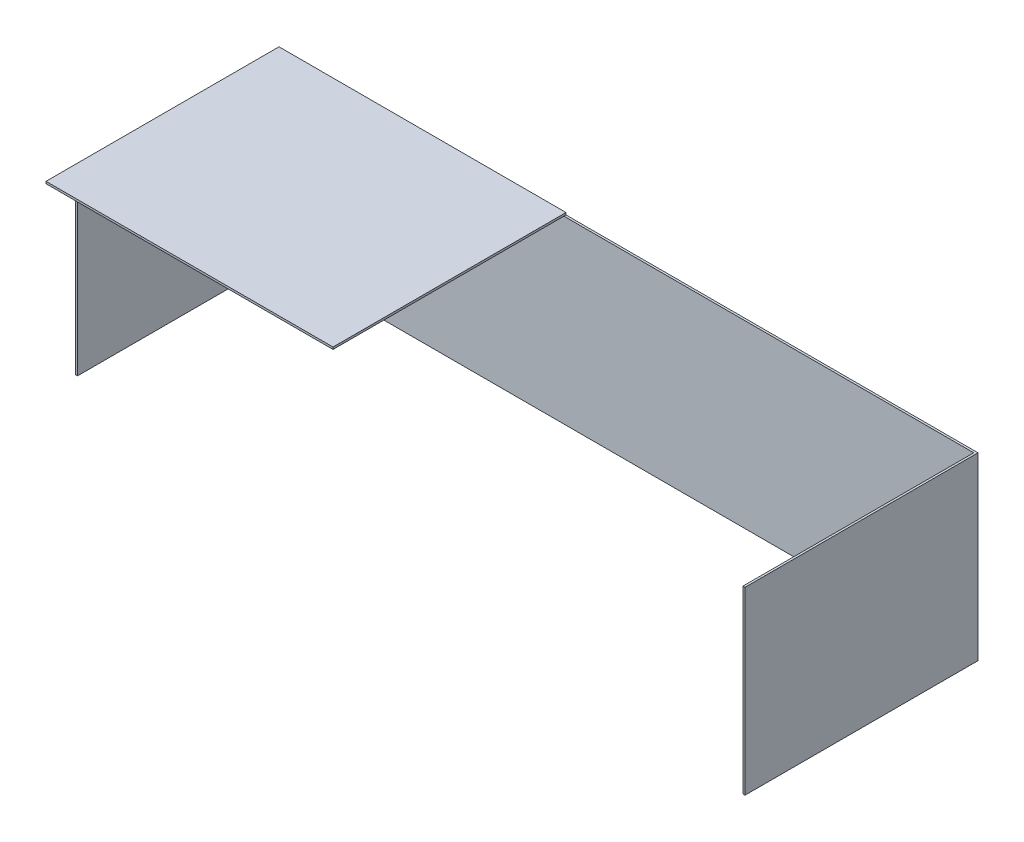
SolidWorks part; units mm, degrees
ref_plane "Alzado" through (0, 0, 0) normal (0, 0, 1) x (1, 0, 0)
ref_plane "Planta" through (0, 0, 0) normal (0, 1, 0) x (1, 0, 0)
ref_plane "Vista lateral" through (0, 0, 0) normal (1, 0, 0) x (0, 0, -1)
sketch "Croquis1" plane through (0, 0, 0) normal (0, 1, 0) x (1, 0, 0)
  line L0 (-305.7378, -89.6137) -> (-305.7378, 100.5793)
  line L1 (350.2622, 100.5793) -> (-305.7378, 100.5793)
  line L2 (352.2622, -117.4207) -> (352.2622, 102.5793)
  line L3 (352.2622, 102.5793) -> (-307.7378, 102.5793)
  line L4 (-307.7378, -89.6137) -> (-307.7378, 102.5793)
  line L5 (352.2622, -117.4207) -> (-307.7378, 102.5793) construction
  line L6 (352.2622, 102.5793) -> (-307.7378, -89.6137) construction
  line L7 (350.2622, -117.4207) -> (350.2622, 100.5793)
  line L8 (-307.7378, -89.6137) -> (-305.7378, -89.6137)
  line L9 (352.2622, -117.4207) -> (350.2622, -117.4207)
  point P0 (0, 0)
  dimension "D1" = 660
  dimension "D2" = 220
  dimension "D3" = 2
extrude "Saliente-Extruir1" add sketch "Croquis1" along normal blind 170
sketch "Croquis2" plane through (0, 170, 0) normal (0, 1, 0) x (1, 0, 0)
  line L0 (348.8815, -117.4207) -> (-305.7378, -117.4207) construction
  line L1 (-307.7378, 102.5793) -> (-36.7257, 102.5793)
  line L2 (-307.7378, 102.5793) -> (-307.7378, -117.4207)
  line L3 (-307.7378, -117.4207) -> (-36.7257, -117.4207)
  line L4 (-36.7257, 102.5793) -> (-36.7257, -117.4207)
extrude "Saliente-Extruir2" add sketch "Croquis2" along normal blind 2
